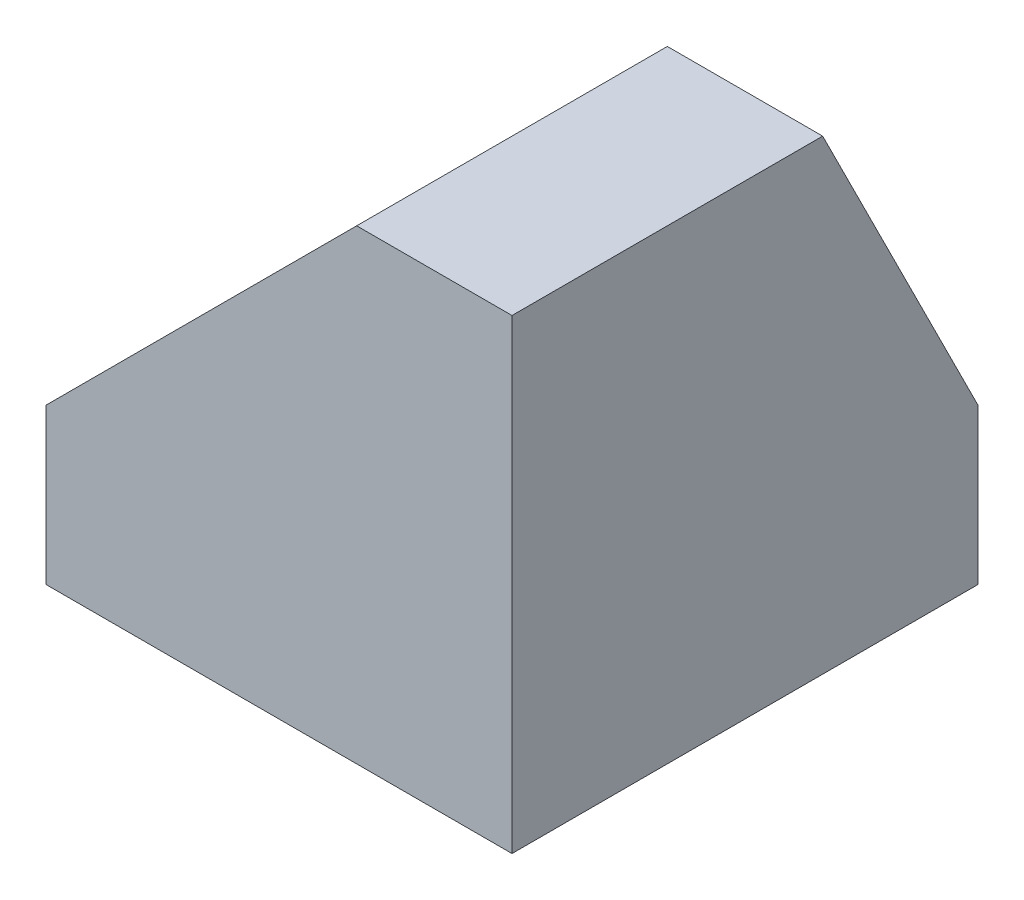
SolidWorks part; units mm, degrees
ref_plane "Alzado" through (0, 0, 0) normal (0, 0, 1) x (1, 0, 0)
ref_plane "Planta" through (0, 0, 0) normal (0, 1, 0) x (1, 0, 0)
ref_plane "Vista lateral" through (0, 0, 0) normal (1, 0, 0) x (0, 0, -1)
sketch "Croquis1" plane through (0, 0, 0) normal (0, 0, 1) x (1, 0, 0)
  line L0 (0, 0) -> (60, 0)
  line L1 (60, 0) -> (60, 60)
  line L3 (0, 20) -> (0, 0)
  line L4 (0, 20) -> (40, 60)
  line L5 (40, 60) -> (60, 60)
  point P3 (0, 0)
  dimension "D1" = 60
  dimension "D2" = 20
  dimension "D3" = 20
  dimension "D4" = 60
extrude "Saliente-Extruir1" add sketch "Croquis1" against normal blind 40
sketch "Croquis2" plane through (0, 0, -40) normal (0, 0, -1) x (-1, 0, 0)
  line L0 (-60, 20) -> (-40, 20)
  line L1 (-60, 0) -> (-60, 60) construction
  line L2 (-40, 20) -> (0, 0)
  line L3 (0, 0) -> (-60, 0)
  line L4 (-60, 0) -> (-60, 20)
  point P10 (-60, 1.1275)
  dimension "D1" = 20
  dimension "D2" = 20
extrude "Saliente-Extruir2" add sketch "Croquis2" along normal blind 20
ref_plane "Plano1" through (60, 0, 0) normal (1, 0, 0) x (0, 0, -1)
sketch "Croquis3" plane through (60, 0, 0) normal (1, 0, 0) x (0, 0, -1)
  line L0 (40, 60) -> (60, 20)
  line L1 (60, 20) -> (40, 20)
  line L2 (40, 20) -> (40, 60)
extrude "Saliente-Extruir3" add sketch "Croquis3" against normal blind 20
